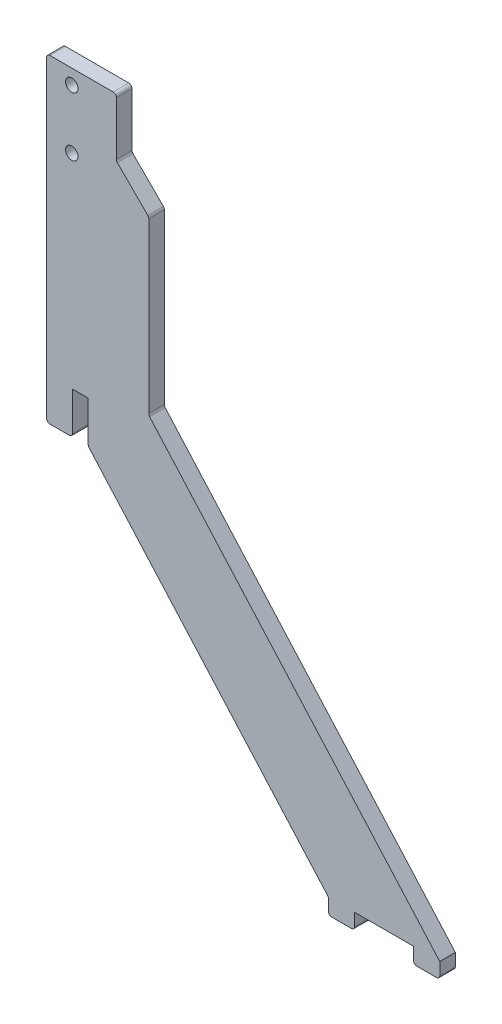
SolidWorks part; units mm, degrees
material "Mahogany"
ref_plane "Front Plane" through (0, 0, 0) normal (0, 0, 1) x (1, 0, 0)
ref_plane "Top Plane" through (0, 0, 0) normal (0, 1, 0) x (1, 0, 0)
ref_plane "Right Plane" through (0, 0, 0) normal (1, 0, 0) x (0, 0, -1)
sketch "Sketch1" plane through (0, 0, 0) normal (0, 0, 1) x (1, 0, 0)
  line L0 (-2.175, 27) -> (17.1184, 27)
  line L1 (18.1184, 26) -> (18.1184, 9.6642)
  line L2 (18.4113, 8.9571) -> (27.7071, -0.3387)
  line L3 (28, -1.0458) -> (28, -52.62)
  line L4 (-3.175, 26) -> (-3.175, -69.4481)
  line L5 (-2.175, -70.4481) -> (3.7625, -70.4481)
  line L6 (9.7774, -70.7322) -> (82.8517, -153)
  line L7 (28.2524, -53.2841) -> (116.825, -153)
  line L8 (90.8517, -153) -> (108.825, -153)
  line L11 (9.525, -70.0681) -> (9.525, -57.7481)
  line L12 (9.525, -57.7481) -> (4.7625, -57.7481)
  line L13 (4.7625, -69.4481) -> (4.7625, -57.7481)
  line L14 (82.8517, -153) -> (82.8517, -156.7625)
  line L15 (19.1184, 10.25) -> (19.1184, 27)
  line L16 (19.1184, 27) -> (35, 27)
  line L17 (35, 27) -> (35, 42)
  line L18 (35, 42) -> (22, 42)
  line L19 (22, 42) -> (12, 32)
  line L20 (12, 32) -> (12, 27)
  line L21 (12, 27) -> (1, 27)
  line L22 (0, 26) -> (0, 1)
  line L23 (1, 0) -> (13.0718, 0)
  line L24 (13.0718, 0) -> (20, -4)
  line L25 (20, -4) -> (31, -4)
  line L26 (31, -4) -> (35, 0)
  line L27 (35, 0) -> (35, 4.5)
  line L28 (35, 4.5) -> (35, 10.25)
  line L29 (35, 10.25) -> (19.1184, 10.25)
  line L30 (19.1184, 10.25) -> (19.1184, 27) construction
  line L31 (19.1184, 27) -> (35, 27) construction
  line L32 (35, 27) -> (35, 42) construction
  line L33 (35, 42) -> (22, 42) construction
  line L34 (22, 42) -> (12, 32) construction
  line L35 (12, 32) -> (12, 27) construction
  line L36 (12, 27) -> (-3.175, 27) construction
  line L37 (0, 26) -> (0, 1) construction
  line L38 (1, 0) -> (13.0718, 0) construction
  line L39 (13.0718, 0) -> (20, -4) construction
  line L40 (20, -4) -> (31, -4) construction
  line L41 (31, -4) -> (35, 0) construction
  line L42 (35, 0) -> (35, 4.5) construction
  line L43 (35, 4.5) -> (35, 10.25) construction
  line L44 (35, 10.25) -> (19.1184, 10.25) construction
  line L45 (83.8517, -157.7625) -> (89.8517, -157.7625)
  line L46 (90.8517, -153) -> (90.8517, -156.7625)
  line L48 (116.825, -153) -> (116.825, -156.7625)
  line L49 (115.825, -157.7625) -> (109.825, -157.7625)
  line L50 (108.825, -153) -> (108.825, -156.7625)
  circle A0 centre (4.5, 22.5) radius 1.8986 construction
  circle A1 centre (4.5, 4.5) radius 1.8986 construction
  arc A2 (1, 27) -> (0, 26) centre (1, 26) ccw
  arc A3 (0, 1) -> (1, 0) centre (1, 1) ccw
  arc A4 (27.7071, -0.3387) -> (28, -1.0458) centre (27, -1.0458) cw
  arc A5 (0, 1) -> (1, 0) centre (1, 1) ccw construction
  circle A6 centre (4.5, 22.5) radius 1.8986
  circle A7 centre (4.5, 4.5) radius 1.8986
  arc A8 (18.1184, 9.6642) -> (18.4113, 8.9571) centre (19.1184, 9.6642) ccw
  arc A9 (17.1184, 27) -> (18.1184, 26) centre (17.1184, 26) cw
  arc A10 (-3.175, 26) -> (-2.175, 27) centre (-2.175, 26) cw
  arc A11 (116.825, -156.7625) -> (115.825, -157.7625) centre (115.825, -156.7625) cw
  arc A12 (109.825, -157.7625) -> (108.825, -156.7625) centre (109.825, -156.7625) cw
  arc A13 (90.8517, -156.7625) -> (89.8517, -157.7625) centre (89.8517, -156.7625) cw
  arc A14 (83.8517, -157.7625) -> (82.8517, -156.7625) centre (83.8517, -156.7625) cw
  arc A15 (28, -52.62) -> (28.2524, -53.2841) centre (29, -52.62) ccw
  arc A16 (9.7774, -70.7322) -> (9.525, -70.0681) centre (10.525, -70.0681) cw
  arc A17 (4.7625, -69.4481) -> (3.7625, -70.4481) centre (3.7625, -69.4481) cw
  arc A18 (-3.175, -69.4481) -> (-2.175, -70.4481) centre (-2.175, -69.4481) ccw
  point P35 (18.1184, 9.25)
  point P61 (82.8517, -157.7625)
  point P64 (28, -53)
  point P67 (9.525, -70.4481)
  point P70 (4.7625, -70.4481)
  dimension "D8" = 1
  dimension "D12" = 180
  dimension "D14" = 1
  dimension "D2" = 1
  dimension "D3" = 1
  dimension "D4" = 135
  dimension "D5" = 80
  dimension "D6" = 7
  dimension "D7" = 3.175
  dimension "D9" = 12.7
  dimension "D10" = 120
  dimension "D11" = 25.4
  dimension "D13" = 12.7
  dimension "D15" = 4.7625
  dimension "D16" = 8
  dimension "D17" = 8
  dimension "D1" = 0
extrude "Boss-Extrude1" add sketch "Sketch1" along normal blind 4.7625
equation "\"D15@Sketch1\"=\"Thickness\""
